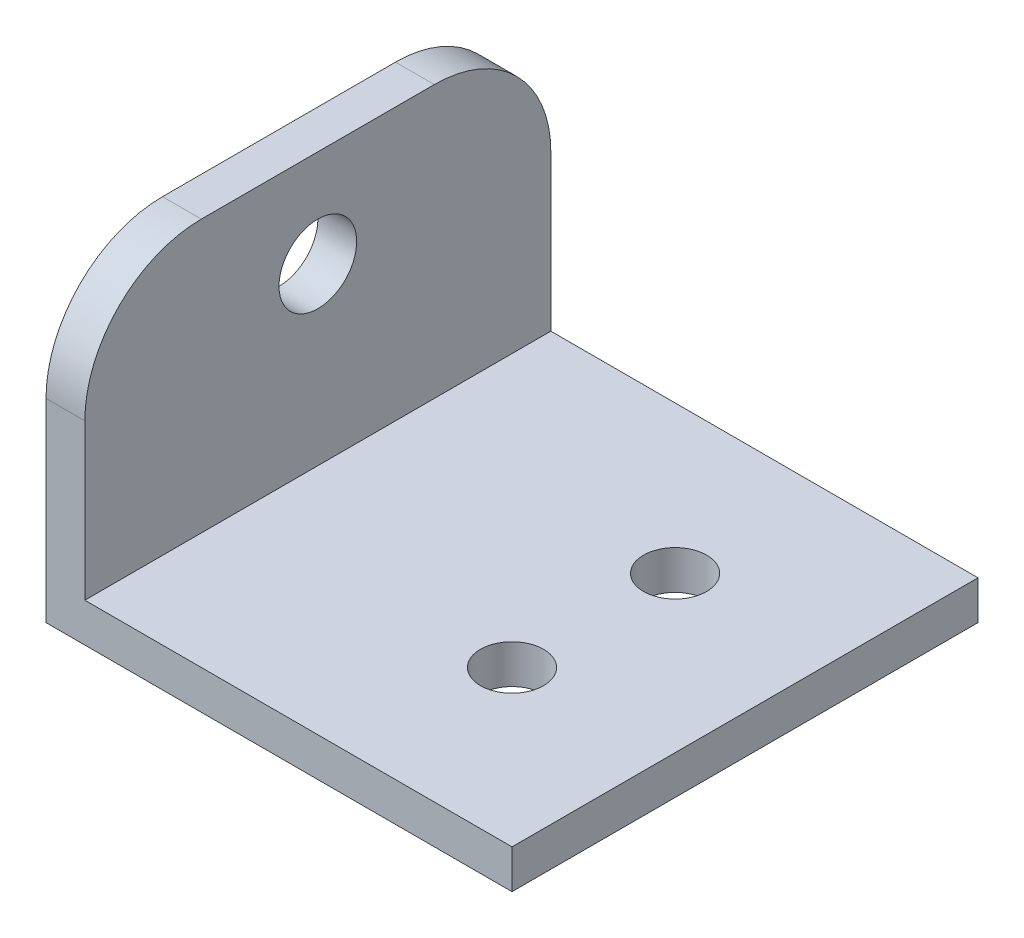
SolidWorks part; units mm, degrees
ref_plane "Front Plane" through (0, 0, 0) normal (0, 0, 1) x (1, 0, 0)
ref_plane "Top Plane" through (0, 0, 0) normal (0, 1, 0) x (1, 0, 0)
ref_plane "Right Plane" through (0, 0, 0) normal (1, 0, 0) x (0, 0, -1)
sketch "Sketch1" plane through (0, 0, 0) normal (0, 0, 1) x (1, 0, 0)
  line L0 (0, 0) -> (0, 25.4)
  line L1 (0, 0) -> (38.1, 0)
  line L2 (3.175, 3.175) -> (38.1, 3.175)
  line L3 (3.175, 3.175) -> (3.175, 25.4)
  line L4 (0, 25.4) -> (3.175, 25.4)
  line L5 (38.1, 0) -> (38.1, 3.175)
  dimension "D1" = 25.4
  dimension "D2" = 38.1
  dimension "D3" = 3.175
extrude "Boss-Extrude1" add sketch "Sketch1" along normal blind 38.1
hole_wizard "13/64 (0.20313) Diameter Hole1" positions "Sketch8" profile "Sketch7" hole size "13/64" standard "ANSI Inch" end condition through all
sketch "Sketch8" plane through (0, 0, 0) normal (0, -1, 0) x (-1, 0, 0)
  line L0 (-25.4, -38.1) -> (-25.4, 0) construction
  line L1 (0, -38.1) -> (-38.1, -38.1) construction
  line L3 (0, -38.1) -> (0, 0) construction
  point P9 (-25.4, -25.4)
  point P11 (-25.4, -12.065)
  dimension "D1" = 12.7
  dimension "D2" = 13.335
  dimension "D3" = 25.4
sketch "Sketch7" plane through (25.4, 0, 25.4) normal (1, 0, 0) x (0, 0, -1)
  line L0 (0, 0) -> (0, 25.4)
  line L1 (0, 25.4) -> (2.5797, 25.4)
  line L2 (2.5797, 25.4) -> (2.5797, 0)
  line L5 (2.5797, 0) -> (0, 0)
  line L11 (0, -6.35) -> (0, 107.95) construction
  dimension "Thru Hole Dia." = 5.1594
  dimension "Thru Hole Depth" = 25.4
hole_wizard "1/4 (0.25) Diameter Hole2" positions "Sketch10" profile "Sketch9" hole size "1/4" standard "ANSI Inch" end condition through all
sketch "Sketch10" plane through (0, 0, 0) normal (-1, 0, 0) x (0, 0, 1)
  line L1 (0, 17.4625) -> (38.1, 17.4625) construction
  line L2 (0, 25.4) -> (0, 0) construction
  line L3 (38.1, 25.4) -> (38.1, 0) construction
  line L5 (38.1, 25.4) -> (0, 25.4) construction
  point P12 (19.05, 17.4625)
  dimension "D1" = 7.9375
sketch "Sketch9" plane through (0, 17.4625, 19.05) normal (0, 1, 0) x (0, 0, 1)
  line L0 (0, 0) -> (0, 38.1)
  line L1 (0, 38.1) -> (3.175, 38.1)
  line L2 (3.175, 38.1) -> (3.175, 0)
  line L5 (3.175, 0) -> (0, 0)
  line L11 (0, -6.35) -> (0, 107.95) construction
  dimension "Thru Hole Dia." = 6.35
  dimension "Thru Hole Depth" = 38.1
fillet "Fillet1" radius 9.525 2 edges at (1.5875, 25.4, 0) (1.5875, 25.4, 38.1)
